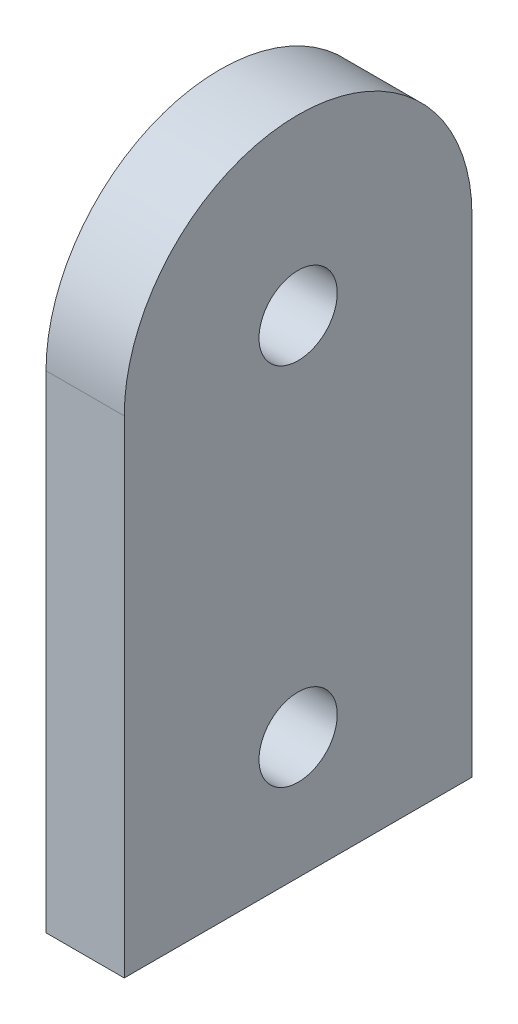
SolidWorks part; units mm, degrees
ref_plane "前视基准面" through (0, 0, 0) normal (0, 0, 1) x (1, 0, 0)
ref_plane "上视基准面" through (0, 0, 0) normal (0, 1, 0) x (1, 0, 0)
ref_plane "右视基准面" through (0, 0, 0) normal (1, 0, 0) x (0, 0, -1)
other "Configuration Table"
sketch "草图1" plane through (0, 0, 0) normal (1, 0, 0) x (0, 0, -1)
  line L1 (0, 0) -> (20, 0)
  line L2 (0, 0) -> (0, 28)
  line L4 (20, 0) -> (20, 28)
  arc A0 (20, 28) -> (0, 28) centre (10, 28) ccw
  circle A1 centre (10, 28) radius 2.25
  circle A2 centre (10, 7) radius 2.25
  dimension "D3" = 4.5
  dimension "D4" = 10
  dimension "D6" = 4.5
  dimension "D1" = 20
  dimension "D2" = 28
  dimension "D5" = 28
  dimension "D7" = 7
  dimension "D8" = 10
extrude "凸台-拉伸1" add sketch "草图1" along normal blind 4.5
